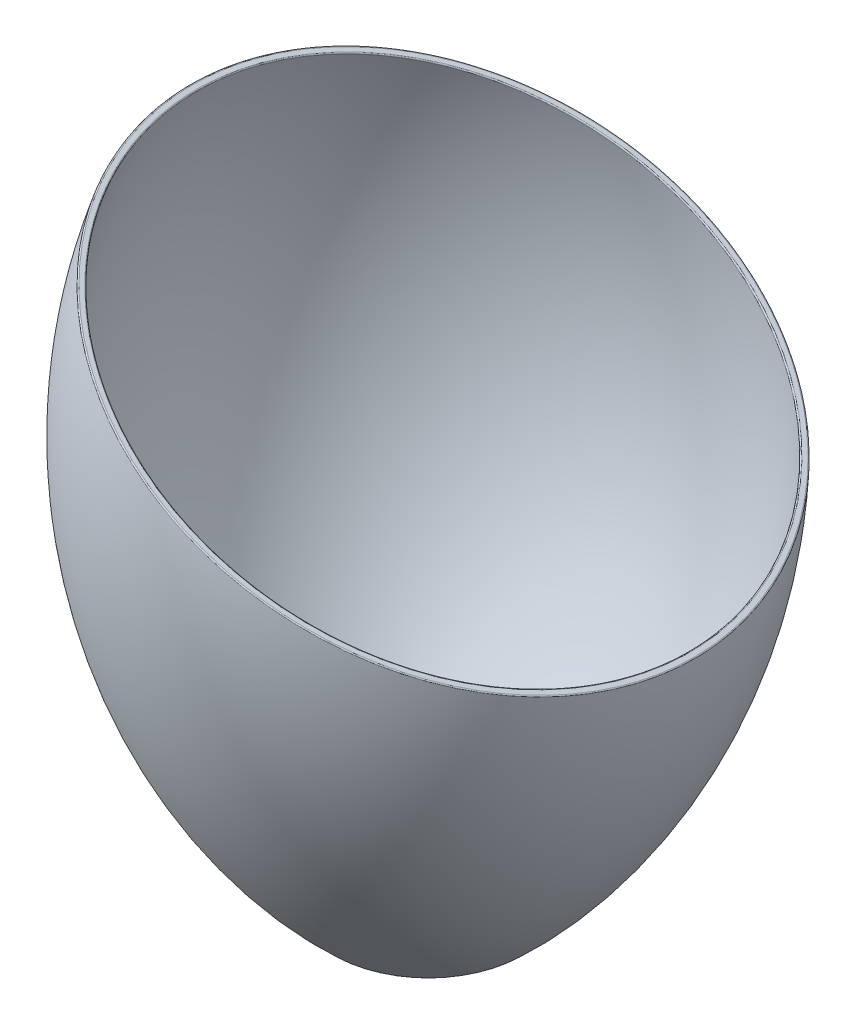
SolidWorks part; units mm, degrees
ref_plane "Front Plane" through (0, 0, 0) normal (0, 0, 1) x (1, 0, 0)
ref_plane "Top Plane" through (0, 0, 0) normal (0, 1, 0) x (1, 0, 0)
ref_plane "Right Plane" through (0, 0, 0) normal (1, 0, 0) x (0, 0, -1)
sketch "Sketch1" plane through (0, 0, 0) normal (0, 0, 1) x (1, 0, 0)
  line L0 (0, 0) -> (36.1172, 0)
  line L1 (0, 0) -> (0, 128.6337) construction
  line L5 (0, 20) -> (51.3281, 20)
  line L6 (0, 20) -> (40, 20) construction
  line L7 (97.2729, 288.7497) -> (100, 290)
  line L8 (0, 20) -> (0, 0)
  line L9 (0, 0) -> (40, 0) construction
  arc A0 (42.9243, 2.6745) -> (100, 290) centre (-127.2547, 185.8113) ccw
  arc A2 (58.8632, 23.4257) -> (97.2729, 288.7497) centre (-127.2547, 185.8113) ccw
  arc A3 (37.9929, 2.2297) -> (97.2729, 288.7497) centre (-127.2547, 185.8113) ccw construction
  arc A4 (40, 0) -> (100, 290) centre (-127.2547, 185.8113) ccw construction
  arc A5 (36.1172, 0) -> (42.9243, 2.6745) centre (36.1172, 10) ccw
  arc A6 (51.3281, 20) -> (58.8632, 23.4257) centre (51.3281, 30) ccw
  point P14 (40, 0)
  dimension "D2" = 40
  dimension "D3" = 290
  dimension "D4" = 250
  dimension "D7" = 10
  dimension "D1" = 200
  dimension "D5" = 3
  dimension "D6" = 20
revolve "Revolve1" add sketch "Sketch1" angle 360 about L1
sketch "Sketch2" plane through (0, 0, 0) normal (0, 0, 1) x (1, 0, 0)
  line L0 (-157.1258, 294.9179) -> (140, 150)
  line L1 (-157.1258, 294.9179) -> (140, 294.9179)
  line L2 (140, 294.9179) -> (140, 150)
  line L3 (100, 290) -> (-100, 290) construction
  point P5 (-65.0304, 310)
  point P6 (-65.0304, 310)
  point P7 (-127.7853, 205.7675)
  point P9 (-157.1258, 354.9179)
  dimension "D1" = 26
  dimension "D2" = 140
  dimension "D3" = 40
extrude "Cut-Extrude1" cut sketch "Sketch2" against normal through all both and the other way through all
fillet "Fillet1" radius 0.5 2 edges at (115.1783, 162.1064, 28.3045) (117.9772, 160.7413, -28.9829)
